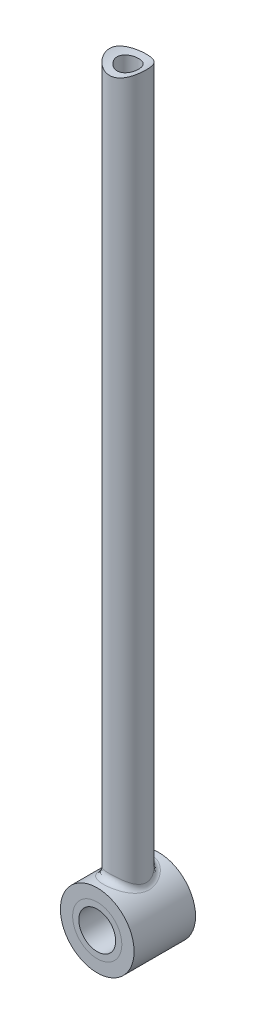
SolidWorks part; units mm, degrees
ref_plane "Front Plane" through (0, 0, 0) normal (0, 0, 1) x (1, 0, 0)
ref_plane "Top Plane" through (0, 0, 0) normal (0, 1, 0) x (1, 0, 0)
ref_plane "Right Plane" through (0, 0, 0) normal (1, 0, 0) x (0, 0, -1)
sketch "Sketch1" plane through (0, 0, 0) normal (0, 1, 0) x (1, 0, 0)
  circle A0 centre (0, 0) radius 3
  dimension "D1" = 6
extrude "Boss-Extrude1" add sketch "Sketch1" along normal blind 57.5 and the other way blind 58
sketch "Sketch2" plane through (0, 0, 0) normal (0, 0, 1) x (1, 0, 0)
  circle A1 centre (0, -63) radius 6
  circle A3 centre (0, -63) radius 4
  circle A4 centre (0, 62.5) radius 6
  circle A5 centre (0, 62.5) radius 3
  dimension "D1" = 62.5
  dimension "D2" = 12
  dimension "D3" = 12
  dimension "D5" = 6
  dimension "D6" = 8
  dimension "D4" = 63
extrude "Boss-Extrude2" add sketch "Sketch2" along normal mid plane 10
sketch "Sketch3" plane through (0, 0, 0) normal (0, 0, 1) x (1, 0, 0)
  circle A2 centre (0, -63) radius 4
  circle A3 centre (0, -63) radius 3
  dimension "D1" = 8
  dimension "D2" = 6
extrude "Boss-Extrude3" add sketch "Sketch3" along normal mid plane 10 separate body
fillet "Fillet1" radius 1 1 edges at (-0.3027, -57.0076, -2.9847)
sketch "Sketch5" plane through (0, 0, 5) normal (0, 0, 1) x (1, 0, 0)
  circle A0 centre (0, 62.5) radius 6
extrude "Cut-Extrude2" cut sketch "Sketch5" against normal blind 10
sketch "Sketch6" plane through (0, 0, 0) normal (0, 1, 0) x (1, 0, 0)
  circle A0 centre (0, 0) radius 1.75
  dimension "D1" = 3.5
extrude "Cut-Extrude3" cut sketch "Sketch6" along normal blind 58 and the other way blind 57
